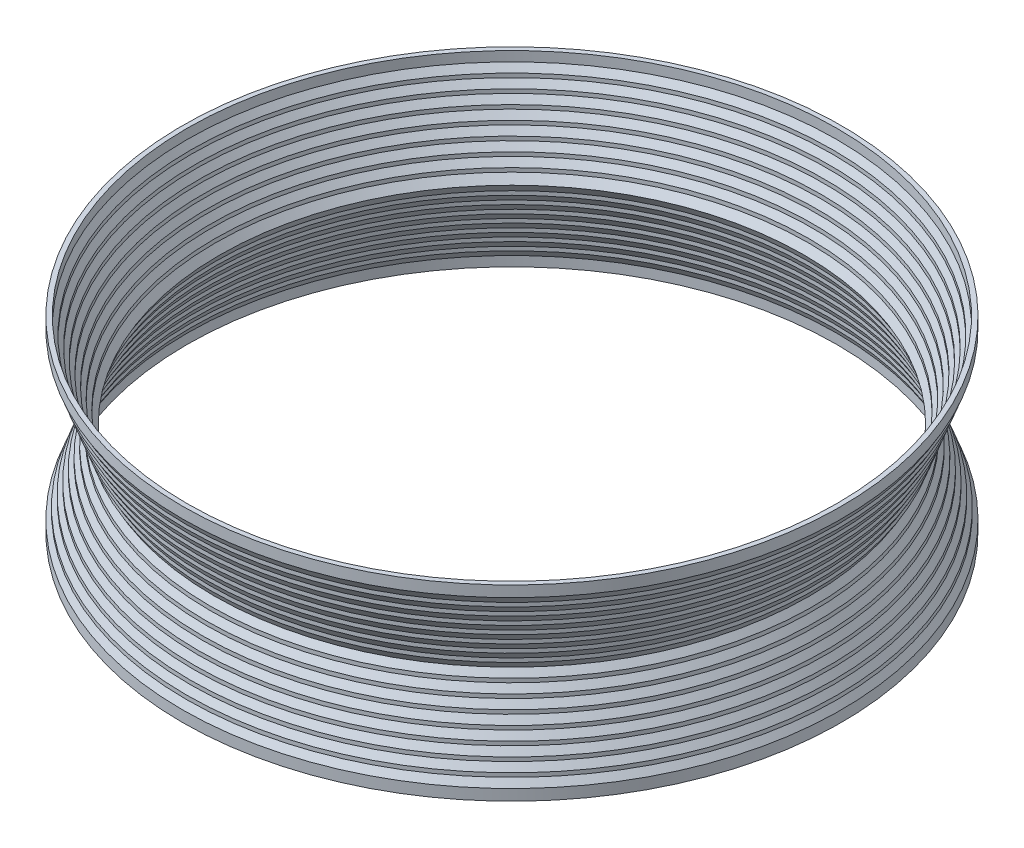
SolidWorks part; units mm, degrees
ref_plane "정면" through (0, 0, 0) normal (0, 0, 1) x (1, 0, 0)
ref_plane "윗면" through (0, 0, 0) normal (0, 1, 0) x (1, 0, 0)
ref_plane "우측면" through (0, 0, 0) normal (1, 0, 0) x (0, 0, -1)
sketch "스케치1" plane through (0, 0, 0) normal (0, 1, 0) x (1, 0, 0)
  circle A7 centre (0, 0) radius 35.8938
  dimension "D2" = 71.7876
extrude "보스-돌출1" add sketch "스케치1" along normal blind 1.2
ref_plane "평면1" through (0, 10.2, 0) normal (0, 1, 0) x (1, 0, 0)
sketch "스케치3" plane through (0, 10.2, 0) normal (0, 1, 0) x (1, 0, 0)
  circle A0 centre (0, 0) radius 27.5887
  dimension "D1" = 55.1775
sketch "스케치4" plane through (0, 0, 0) normal (1, 0, 0) x (0, 0, -1)
  line L1 (27.5887, 10.2) -> (-27.5887, 10.2) construction
  line L2 (0, 10.2) -> (0, 1.2) construction
  line L3 (35.8938, 1.2) -> (-35.8938, 1.2) construction
  line L4 (-35.8938, 1.2) -> (-35.4608, 1.95)
  line L5 (-35.4608, 1.95) -> (-35.4608, 2.38)
  line L6 (-35.4608, 2.38) -> (-35.0278, 3.13)
  line L7 (-35.8938, 1.2) -> (-30.6977, 10.2) construction
  line L8 (0, 10.2) -> (-30.6977, 10.2) construction
  line L9 (-35.0278, 3.13) -> (-35.0278, 3.56)
  line L10 (-35.0278, 3.56) -> (-34.5948, 4.31)
  line L11 (-34.5948, 4.31) -> (-34.5948, 4.74)
  line L12 (-34.5948, 4.74) -> (-34.1618, 5.49)
  line L13 (0, 10.2) -> (30.6977, 10.2) construction
  line L15 (0, 10.2) -> (0, 1.2)
  line L16 (-35.8938, 1.2) -> (0, 1.2)
  line L17 (-34.1618, 5.49) -> (-34.1618, 5.92)
  line L18 (-34.1618, 5.92) -> (-33.7287, 6.67)
  line L20 (-33.7287, 6.67) -> (-33.7287, 7.1)
  line L21 (-33.7287, 7.1) -> (-33.2957, 7.85)
  line L22 (-33.2957, 7.85) -> (-33.2957, 8.28)
  line L23 (-33.2957, 8.28) -> (-32.8627, 9.03)
  line L24 (-32.8627, 9.03) -> (-32.8627, 9.46)
  line L25 (-32.8627, 9.46) -> (-32.4297, 10.21)
  line L26 (-32.4297, 10.21) -> (0, 10.2)
  dimension "D1" = 0.75
  dimension "D2" = 60
  dimension "D3" = 0.43
revolve "회전1" add sketch "스케치4" angle 360 about L15
mirror "대칭 복사1" about plane through (0, 10.2, 0) normal (0, 1, 0) of "보스-돌출1", "회전1"
shell "쉘1" thickness 0.5
